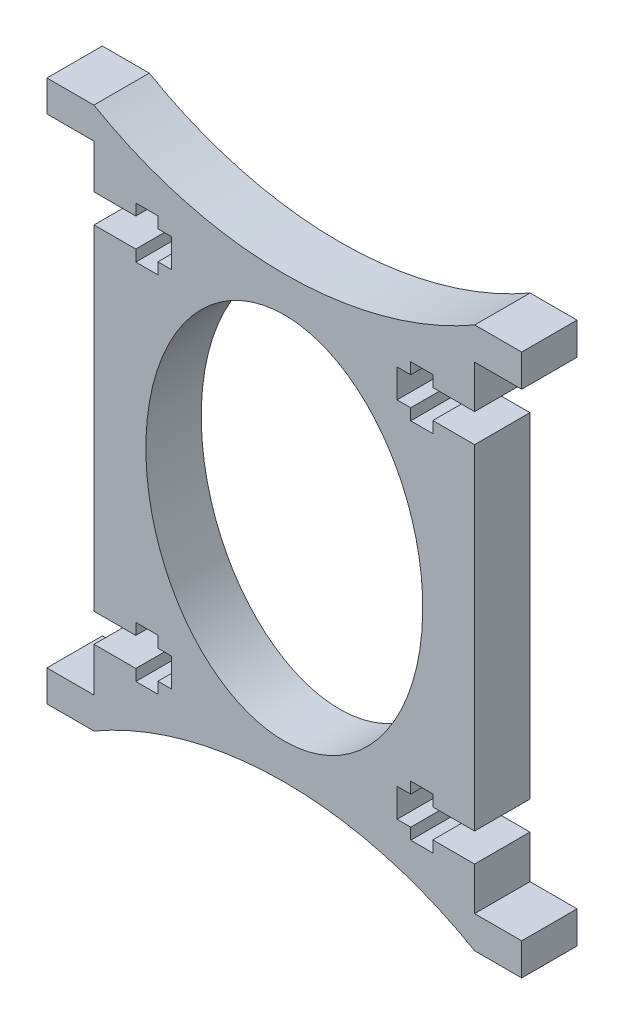
SolidWorks part; units mm, degrees
material "Acrylic (Medium-high impact)"
ref_plane "Front Plane" through (0, 0, 0) normal (0, 0, 1) x (1, 0, 0)
ref_plane "Top Plane" through (0, 0, 0) normal (0, 1, 0) x (1, 0, 0)
ref_plane "Right Plane" through (0, 0, 0) normal (1, 0, 0) x (0, 0, -1)
sketch "Sketch1" plane through (0, 0, 0) normal (0, 0, 1) x (1, 0, 0)
  line L0 (742.1979, 459.1011) -> (700.9669, 459.1011) construction
  line L1 (737.6724, 439.4261) -> (742.1973, 439.4261) construction
  line L2 (737.6724, 439.4261) -> (737.6724, 437.8782) construction
  line L3 (737.6724, 440.9739) -> (737.6724, 439.4261) construction
  line L4 (736.4752, 436.6538) -> (736.4752, 439.4261) construction
  line L5 (733.7999, 439.4261) -> (742.1973, 439.4261) construction
  line L6 (736.4752, 442.1983) -> (736.4752, 439.4261) construction
  line L7 (735.2781, 436.6538) -> (737.6724, 436.6538)
  line L8 (700.9669, 459.1011) -> (700.9669, 440.9739)
  line L9 (706.6895, 442.1983) -> (706.6895, 439.4261) construction
  line L10 (735.2781, 442.1983) -> (737.6724, 442.1983)
  line L11 (733.7999, 440.9739) -> (733.7999, 437.8782)
  line L12 (742.1979, 437.8782) -> (742.1979, 433.2256)
  line L13 (742.1979, 437.8782) -> (737.6724, 437.8782)
  line L14 (737.6724, 440.9739) -> (742.1979, 440.9739)
  line L15 (747.2997, 429.7361) -> (747.2997, 433.2256)
  line L16 (742.2131, 429.7361) -> (747.2997, 429.7361)
  line L17 (709.3648, 439.4261) -> (700.9669, 439.4261) construction
  line L18 (707.8867, 436.6538) -> (707.8867, 437.8782)
  line L19 (707.8867, 440.9739) -> (709.3648, 440.9739)
  line L20 (707.8867, 437.8782) -> (709.3648, 437.8782)
  line L21 (707.8867, 440.9739) -> (707.8867, 442.1983)
  line L22 (706.6895, 436.6538) -> (706.6895, 439.4261) construction
  line L23 (705.4923, 436.6538) -> (705.4923, 437.8782)
  line L24 (705.4923, 440.9739) -> (705.4923, 442.1983)
  line L25 (705.4923, 440.9739) -> (705.4923, 439.4261) construction
  line L26 (705.4923, 439.4261) -> (705.4923, 437.8782) construction
  line L27 (695.8656, 433.1161) -> (700.9669, 433.1161)
  line L28 (700.9523, 429.7361) -> (695.8656, 429.7361)
  line L29 (695.8656, 429.7361) -> (695.8656, 433.1161)
  line L30 (705.4923, 440.9739) -> (700.9669, 440.9739)
  line L31 (700.9669, 437.8782) -> (705.4923, 437.8782)
  line L32 (700.9669, 437.8782) -> (700.9669, 433.1161)
  line L33 (705.4923, 439.4261) -> (700.9669, 439.4261) construction
  line L34 (709.3648, 440.9739) -> (709.3648, 437.8782)
  line L35 (747.2997, 433.2256) -> (742.1979, 433.2256)
  line L36 (737.6724, 440.9739) -> (737.6724, 442.1983)
  line L37 (737.6724, 436.6538) -> (737.6724, 437.8782)
  line L38 (735.2781, 440.9739) -> (735.2781, 442.1983)
  line L39 (735.2781, 437.8782) -> (733.7999, 437.8782)
  line L40 (735.2781, 440.9739) -> (733.7999, 440.9739)
  line L41 (735.2781, 436.6538) -> (735.2781, 437.8782)
  line L42 (742.1979, 459.1011) -> (742.1979, 440.9739)
  line L43 (705.4923, 478.7761) -> (700.9669, 478.7761) construction
  line L44 (707.8867, 442.1983) -> (705.4923, 442.1983)
  line L45 (705.4923, 478.7761) -> (705.4923, 480.3239) construction
  line L46 (705.4923, 477.2282) -> (705.4923, 478.7761) construction
  line L47 (706.6895, 481.5483) -> (706.6895, 478.7761) construction
  line L48 (709.3648, 478.7761) -> (700.9669, 478.7761) construction
  line L49 (706.6895, 476.0038) -> (706.6895, 478.7761) construction
  line L50 (736.4752, 476.0038) -> (736.4752, 478.7761) construction
  line L51 (733.7999, 478.7761) -> (742.1973, 478.7761) construction
  line L52 (736.4752, 481.5483) -> (736.4752, 478.7761) construction
  line L53 (737.6724, 477.2282) -> (737.6724, 478.7761) construction
  line L54 (737.6724, 478.7761) -> (737.6724, 480.3239) construction
  line L55 (737.6724, 478.7761) -> (742.1973, 478.7761) construction
  line L56 (707.8867, 481.5483) -> (705.4923, 481.5483)
  line L57 (707.8867, 476.0038) -> (705.4923, 476.0038)
  line L58 (742.1979, 459.1011) -> (742.1979, 477.2282)
  line L59 (735.2781, 481.5483) -> (735.2781, 480.3239)
  line L61 (707.8867, 436.6538) -> (705.4923, 436.6538)
  line L62 (735.2781, 477.2282) -> (733.7999, 477.2282)
  line L63 (735.2781, 480.3239) -> (733.7999, 480.3239)
  line L64 (735.2781, 477.2282) -> (735.2781, 476.0038)
  line L65 (737.6724, 481.5483) -> (737.6724, 480.3239)
  line L66 (737.6724, 477.2282) -> (737.6724, 476.0038)
  line L67 (747.2997, 484.9765) -> (742.1979, 484.9765)
  line L68 (709.3648, 477.2282) -> (709.3648, 480.3239)
  line L69 (700.9669, 480.3239) -> (700.9669, 485.0861)
  line L70 (700.9669, 480.3239) -> (705.4923, 480.3239)
  line L71 (705.4923, 477.2282) -> (700.9669, 477.2282)
  line L72 (695.8656, 488.4661) -> (695.8656, 485.0861)
  line L73 (700.9523, 488.4661) -> (695.8656, 488.4661)
  line L74 (695.8656, 485.0861) -> (700.9669, 485.0861)
  line L75 (705.4923, 477.2282) -> (705.4923, 476.0038)
  line L76 (705.4923, 481.5483) -> (705.4923, 480.3239)
  line L77 (707.8867, 477.2282) -> (707.8867, 476.0038)
  line L78 (707.8867, 480.3239) -> (709.3648, 480.3239)
  line L79 (707.8867, 477.2282) -> (709.3648, 477.2282)
  line L80 (707.8867, 481.5483) -> (707.8867, 480.3239)
  line L81 (742.2131, 488.4661) -> (747.2997, 488.4661)
  line L82 (747.2997, 488.4661) -> (747.2997, 484.9765)
  line L83 (737.6724, 477.2282) -> (742.1979, 477.2282)
  line L84 (742.1979, 480.3239) -> (737.6724, 480.3239)
  line L85 (742.1979, 480.3239) -> (742.1979, 484.9765)
  line L86 (733.7999, 477.2282) -> (733.7999, 480.3239)
  line L87 (735.2781, 476.0038) -> (737.6724, 476.0038)
  line L88 (700.9669, 459.1011) -> (700.9669, 477.2282)
  line L89 (735.2781, 481.5483) -> (737.6724, 481.5483)
  line L90 (721.5824, 459.1011) -> (706.5824, 459.1011) construction
  line L91 (700.9669, 480.3239) -> (700.9669, 477.2282) construction
  line L92 (700.9669, 485.0861) -> (700.9523, 488.4661) construction
  line L93 (700.9669, 433.1161) -> (700.9523, 429.7361) construction
  arc A0 (700.9523, 488.4661) -> (742.2131, 488.4661) centre (721.5827, 524.2062) ccw
  arc A1 (700.9523, 429.7361) -> (742.2131, 429.7361) centre (721.5827, 393.996) cw
  ellipse E0 centre (721.5824, 459.1011) end of major axis (721.5824, 479.1011) minor radius 15
  point P38 (721.5824, 459.1011)
  point P102 (700.9596, 486.7761)
  point P103 (700.9596, 431.4261)
  dimension "D1" = 55.35
  dimension "D2" = 3.0957
  dimension "D3" = 3.38
  dimension "D4" = 8
extrude "Boss-Extrude1" add sketch "Sketch1" along normal blind 6
